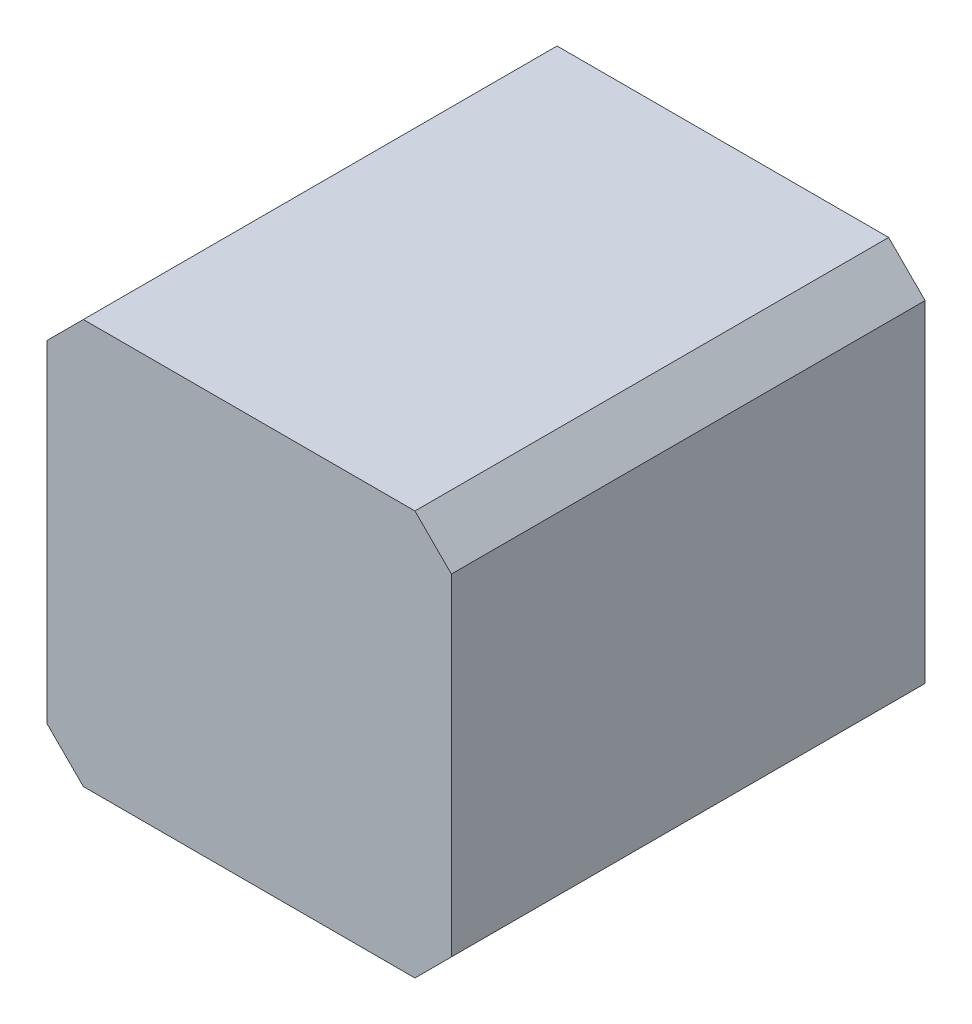
SolidWorks part; units mm, degrees
ref_plane "Front Plane" through (0, 0, 0) normal (0, 0, 1) x (1, 0, 0)
ref_plane "Top Plane" through (0, 0, 0) normal (0, 1, 0) x (1, 0, 0)
ref_plane "Right Plane" through (0, 0, 0) normal (1, 0, 0) x (0, 0, -1)
sketch "Sketch1" plane through (0, 0, 0) normal (0, 0, 1) x (1, 0, 0)
  line L1 (14.097, -14.097) -> (-14.097, -14.097)
  line L2 (14.097, -14.097) -> (14.097, 14.097)
  line L3 (14.097, 14.097) -> (-14.097, 14.097)
  line L4 (-14.097, -14.097) -> (-14.097, 14.097)
  line L5 (14.097, -14.097) -> (-14.097, 14.097) construction
  line L6 (14.097, 14.097) -> (-14.097, -14.097) construction
  point P0 (0, 0)
  dimension "D1" = 28.194
extrude "Boss-Extrude1" add sketch "Sketch1" along normal blind 33.02
sketch "Sketch3" plane through (0, 0, 0) normal (0, 0, -1) x (-1, 0, 0)
  circle A0 centre (0, 0) radius 10.9982
  dimension "D1" = 21.9964
extrude "Boss-Extrude2" add sketch "Sketch3" along normal blind 1.778
sketch "Sketch5" plane through (0, 0, -1.778) normal (0, 0, -1) x (-1, 0, 0)
  circle A0 centre (0, 0) radius 3.175
  dimension "D1" = 6.35
extrude "Cut-Extrude1" cut sketch "Sketch5" against normal blind 5.08
chamfer "Chamfer1" distance 2.54 angle 45 4 edges at (14.097, 14.097, 16.51) (-14.097, 14.097, 16.51) (-14.097, -14.097, 16.51) (14.097, -14.097, 16.51)
